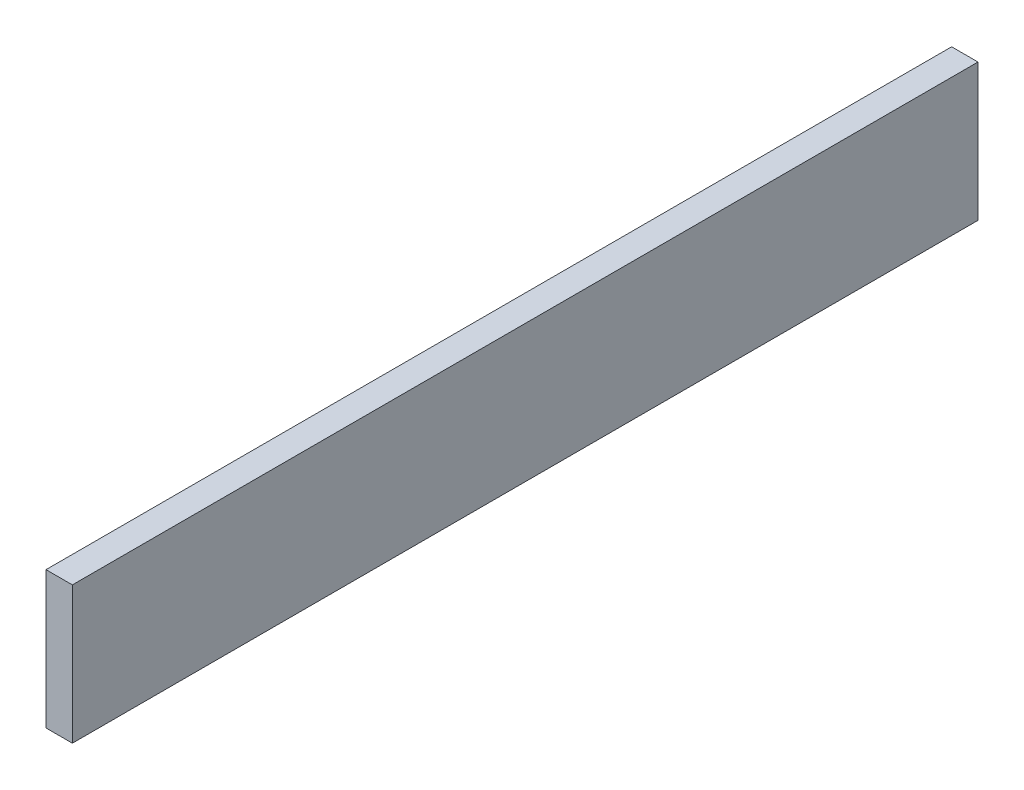
SolidWorks part; units mm, degrees
ref_plane "Front Plane" through (0, 0, 0) normal (1, 0, 0) x (0, 1, 0)
ref_plane "Top Plane" through (0, 0, 0) normal (0, 0, 1) x (0, 1, 0)
ref_plane "Right Plane" through (0, 0, 0) normal (0, 1, 0) x (-1, 0, 0)
sketch "Sketch1" plane through (0, 0, 0) normal (1, 0, 0) x (0, 1, 0)
  line L0 (-774.1, 3162.3) -> (-774.1, 3048.381)
  line L1 (-774.1, 3048.381) -> (-791.0195, 3048.381)
  line L3 (-800.1, 3048.381) -> (-800.1, 2990.596)
  line L4 (-800.1, 2990.596) -> (-774.1, 2990.596)
  line L5 (-774.1, 2990.596) -> (-774.1, 3048.381)
  line L14 (-804.2275, 2990.596) -> (-804.2275, 2922.905)
  line L15 (-804.2275, 2922.905) -> (-691.9595, 2922.905)
  line L16 (-691.9595, 2922.905) -> (-691.9595, 2990.596)
  line L17 (-691.9595, 2990.596) -> (-705.1675, 2990.596)
  line L18 (-705.1675, 2990.596) -> (-705.1675, 3048.381)
  line L19 (-705.1675, 3048.381) -> (-696.087, 3048.381)
  line L20 (-696.087, 3048.381) -> (-696.087, 3092.958)
  line L21 (-696.087, 3092.958) -> (-701.04, 3092.958)
  line L22 (-701.04, 3092.958) -> (-701.04, 3162.3)
  line L23 (-701.04, 3162.3) -> (-800.1, 3162.3)
  line L24 (-800.1, 3162.3) -> (-800.1, 3048.381)
  line L25 (-800.1, 3048.381) -> (-791.0195, 3048.381)
  line L26 (-791.0195, 3048.381) -> (-791.0195, 2990.596)
  line L27 (-791.0195, 2990.596) -> (-804.2275, 2990.596)
  line L28 (-804.2275, 2990.596) -> (-804.2275, 2922.905)
  line L29 (-804.2275, 2922.905) -> (-691.9595, 2922.905)
  line L30 (-691.9595, 2922.905) -> (-691.9595, 2990.596)
  line L31 (-691.9595, 2990.596) -> (-705.1675, 2990.596)
  line L32 (-705.1675, 2990.596) -> (-705.1675, 3048.381)
  line L33 (-705.1675, 3048.381) -> (-696.087, 3048.381)
  line L34 (-696.087, 3048.381) -> (-696.087, 3092.958)
  line L35 (-696.087, 3092.958) -> (-701.04, 3092.958)
  line L36 (-701.04, 3092.958) -> (-701.04, 3162.3)
  line L37 (-701.04, 3162.3) -> (-800.1, 3162.3)
  line L38 (-800.1, 3162.3) -> (-800.1, 3048.381)
  line L39 (-800.1, 3048.381) -> (-791.0195, 3048.381)
  line L40 (-791.0195, 3048.381) -> (-791.0195, 2990.596)
  line L41 (-791.0195, 2990.596) -> (-804.2275, 2990.596)
  dimension "D2" = 26
  dimension "D1" = 0
extrude "Boss-Extrude1" add sketch "Sketch1" along normal blind 5 from offset 50 contours L38 L39 L1 L0 L37 | L1 L40 L4 L5 | L40 L39 L3 L4
